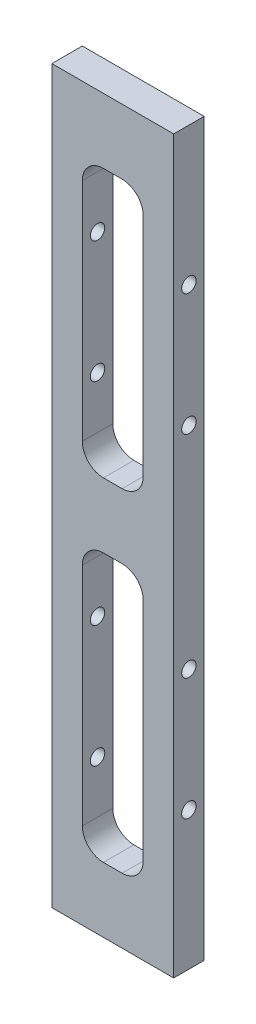
SolidWorks part; units mm, degrees
material "6061-T6 (SS)"
ref_plane "Front Plane" through (0, 0, 0) normal (0, 0, 1) x (1, 0, 0)
ref_plane "Top Plane" through (0, 0, 0) normal (0, 1, 0) x (1, 0, 0)
ref_plane "Right Plane" through (0, 0, 0) normal (1, 0, 0) x (0, 0, -1)
sketch "Sketch1" plane through (0, 0, 0) normal (0, 0, 1) x (1, 0, 0)
  line L1 (-9.525, -57.15) -> (9.525, -57.15)
  line L2 (-9.525, -57.15) -> (-9.525, 57.15)
  line L3 (-9.525, 57.15) -> (9.525, 57.15)
  line L4 (9.525, -57.15) -> (9.525, 57.15)
  line L5 (-9.525, -57.15) -> (9.525, 57.15) construction
  line L6 (-9.525, 57.15) -> (9.525, -57.15) construction
  point P0 (0, 0)
  dimension "D1" = 19.05
  dimension "D2" = 114.3
extrude "Boss-Extrude1" add sketch "Sketch1" along normal blind 4.7625
sketch "Sketch2" plane through (0, 0, 4.7625) normal (0, 0, 1) x (1, 0, 0)
  line L0 (-9.525, 0) -> (9.525, 0) construction
  line L1 (-9.525, 57.15) -> (-9.525, -57.15) construction
  line L2 (9.525, -57.15) -> (9.525, 57.15) construction
  line L3 (0, 57.15) -> (0, 0) construction
  line L4 (9.525, 57.15) -> (-9.525, 57.15) construction
  line L5 (-4.7625, -46.99) -> (4.7625, -5.08) construction
  line L6 (-4.7625, 5.08) -> (4.7625, 5.08)
  line L7 (-4.7625, 5.08) -> (-4.7625, 46.99)
  line L8 (-4.7625, 46.99) -> (4.7625, 46.99)
  line L9 (4.7625, 5.08) -> (4.7625, 46.99)
  line L10 (-4.7625, 5.08) -> (4.7625, 46.99) construction
  line L11 (-4.7625, 46.99) -> (4.7625, 5.08) construction
  line L12 (-4.7625, -5.08) -> (4.7625, -46.99) construction
  line L13 (4.7625, -5.08) -> (4.7625, -46.99)
  line L14 (-4.7625, -46.99) -> (4.7625, -46.99)
  line L15 (-4.7625, -5.08) -> (-4.7625, -46.99)
  line L16 (-4.7625, -5.08) -> (4.7625, -5.08)
  point P11 (0, 26.035)
  point P20 (0, -26.035)
  dimension "D1" = 4.7625
  dimension "D2" = 5.08
  dimension "D3" = 10.16
extrude "Cut-Extrude1" cut sketch "Sketch2" against normal through all
fillet "Fillet1" radius 3.302 8 edges at (-4.7625, -46.99, 2.3813) (4.7625, -46.99, 2.3813) (-4.7625, -5.08, 2.3813) (4.7625, -5.08, 2.3813) (-4.7625, 5.08, 2.3813) (4.7625, 5.08, 2.3813) (4.7625, 46.99, 2.3813) (-4.7625, 46.99, 2.3813)
hole_wizard "#4-40 Tapped Hole1" positions "Sketch4" profile "Sketch5" tap size "#4-40" standard "ANSI Inch" end condition through all
sketch "Sketch4" plane through (9.525, 0, 0) normal (1, 0, 0) x (0, 0, -1)
  line L0 (-2.3813, 57.15) -> (-2.3813, -57.15) construction
  line L1 (-4.7625, 57.15) -> (0, 57.15) construction
  line L2 (-4.7625, -57.15) -> (0, -57.15) construction
  line L3 (0, -57.15) -> (0, 57.15) construction
  point P9 (-2.3812, 35.56)
  point P23 (-2.3812, 16.51)
  point P29 (-2.3812, -16.51)
  point P31 (-2.3812, -35.56)
  point P44 (0, 0)
  dimension "D1" = 19.05
  dimension "D2" = 16.51
  dimension "D3" = 16.51
  dimension "D4" = 19.05
sketch "Sketch5" plane through (9.525, 35.56, 2.3812) normal (0, 1, 0) x (0, 0, -1)
  line L0 (0, 0) -> (0, 19.05)
  line L1 (0, 19.05) -> (1.1303, 19.05)
  line L2 (1.1303, 19.05) -> (1.1303, 0)
  line L5 (1.1303, 0) -> (0, 0)
  line L11 (0, -6.35) -> (0, 107.95) construction
  dimension "Thru Tap Drill Dia." = 2.2606
  dimension "Thru Tap Drill Depth" = 19.05
cosmetic thread "Hole Thread1" parameters "D2"=2.8448
cosmetic thread "Hole Thread2" parameters "D2"=2.8448
cosmetic thread "Hole Thread3" parameters "D2"=2.8448
cosmetic thread "Hole Thread4" parameters "D2"=2.8448
